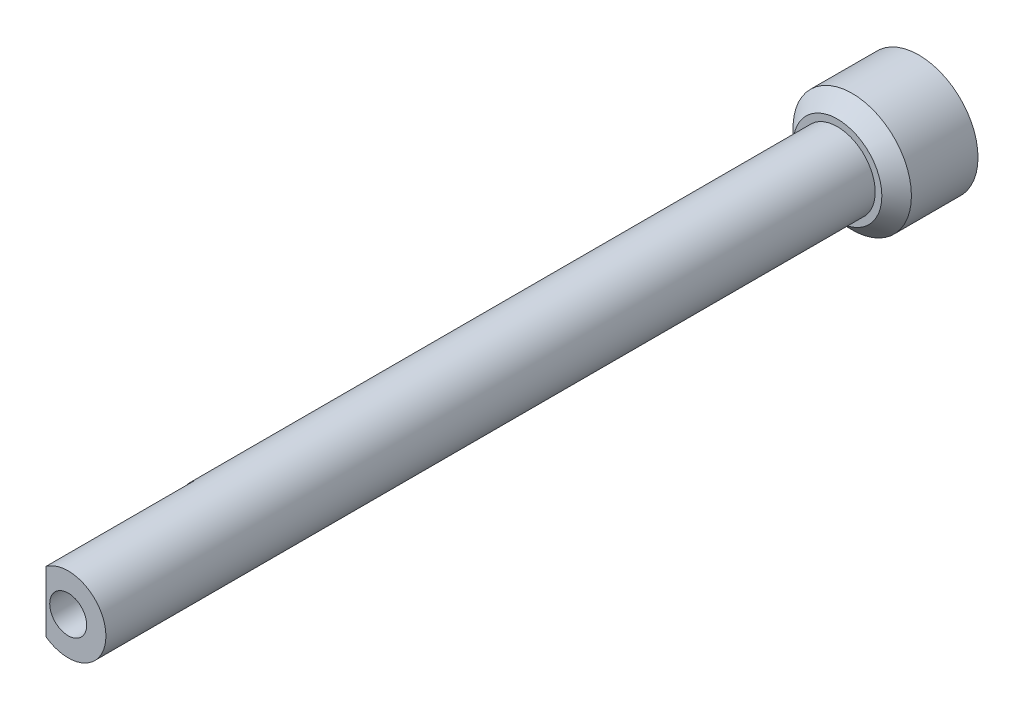
SolidWorks part; units mm, degrees
ref_plane "前视基准面" through (0, 0, 0) normal (0, 0, 1) x (1, 0, 0)
ref_plane "上视基准面" through (0, 0, 0) normal (0, 1, 0) x (1, 0, 0)
ref_plane "右视基准面" through (0, 0, 0) normal (1, 0, 0) x (0, 0, -1)
other "Configuration Table"
sketch "草图1" plane through (0, 0, 0) normal (0, 0, 1) x (1, 0, 0)
  circle A0 centre (0, 0) radius 1.25
  circle A1 centre (0, 0) radius 2.55
  dimension "D1" = 2.5
  dimension "D2" = 5.1
extrude "凸台-拉伸1" add sketch "草图1" along normal blind 52
sketch "草图2" plane through (0, 0, 0) normal (0, 0, -1) x (-1, 0, 0)
  circle A0 centre (0, 0) radius 4
  circle A1 centre (0, 0) radius 1.25 construction
  circle A2 centre (0, 0) radius 1.25
  dimension "D1" = 8
extrude "凸台-拉伸2" add sketch "草图2" along normal blind 3
sketch "草图4" plane through (0, 0, 52) normal (0, 0, 1) x (1, 0, 0)
  line L1 (-1.5, 2.55) -> (1.5, 2.55)
  line L2 (-1.5, 2.55) -> (-1.5, -2.55)
  line L3 (-1.5, -2.55) -> (1.5, -2.55)
  line L4 (1.5, 2.55) -> (1.5, -2.55)
  line L5 (-1.5, 2.55) -> (1.5, -2.55) construction
  line L6 (-1.5, -2.55) -> (1.5, 2.55) construction
  circle A0 centre (0, 0) radius 2.55 construction
  circle A1 centre (0, 0) radius 1.25 construction
  circle A2 centre (0, 0) radius 2.55
  point P0 (0, 0)
  dimension "D1" = 1.5
extrude "切除-拉伸2" cut sketch "草图4" against normal blind 10 contours L2 L5
sketch "草图6" plane through (0, 0, 0) normal (0, 1, 0) x (1, 0, 0)
  line L0 (0, 3) -> (0, 1.2)
  line L1 (4, 3) -> (-4, 3) construction
  line L3 (2.5, 3) -> (0, 3)
  line L4 (0, 1.2) -> (2.2, 1.2)
  line L5 (2.2, 1.2) -> (2.5, 3)
  dimension "D1" = 1.8
  dimension "D2" = 2.5
  dimension "D3" = 2.2
revolve "切除-旋转1" cut sketch "草图6" angle 360 about L0
sketch "草图8" plane through (0, 0, 0) normal (0, 1, 0) x (1, 0, 0)
  line L0 (0, 0) -> (0, 3) construction
  line L1 (4, 3) -> (-4, 3) construction
  line L2 (4, 1) -> (3, 0)
  line L3 (4, 0) -> (4, 3) construction
  line L4 (-4, 0) -> (4, 0) construction
  line L5 (4, 1) -> (4, 0)
  line L6 (4, 0) -> (3, 0)
  dimension "D1" = 3
  dimension "D2" = 1
revolve "切除-旋转3" cut sketch "草图8" angle 360 about L0
sketch "草图9" plane through (0, 0, -3) normal (0, 0, -1) x (-1, 0, 0)
  circle A0 centre (0, 0) radius 4
  circle A1 centre (0, 0) radius 2.6
  dimension "D1" = 5.2
  dimension "D2" = 8
extrude "凸台-拉伸3" add sketch "草图9" along normal blind 2.5
